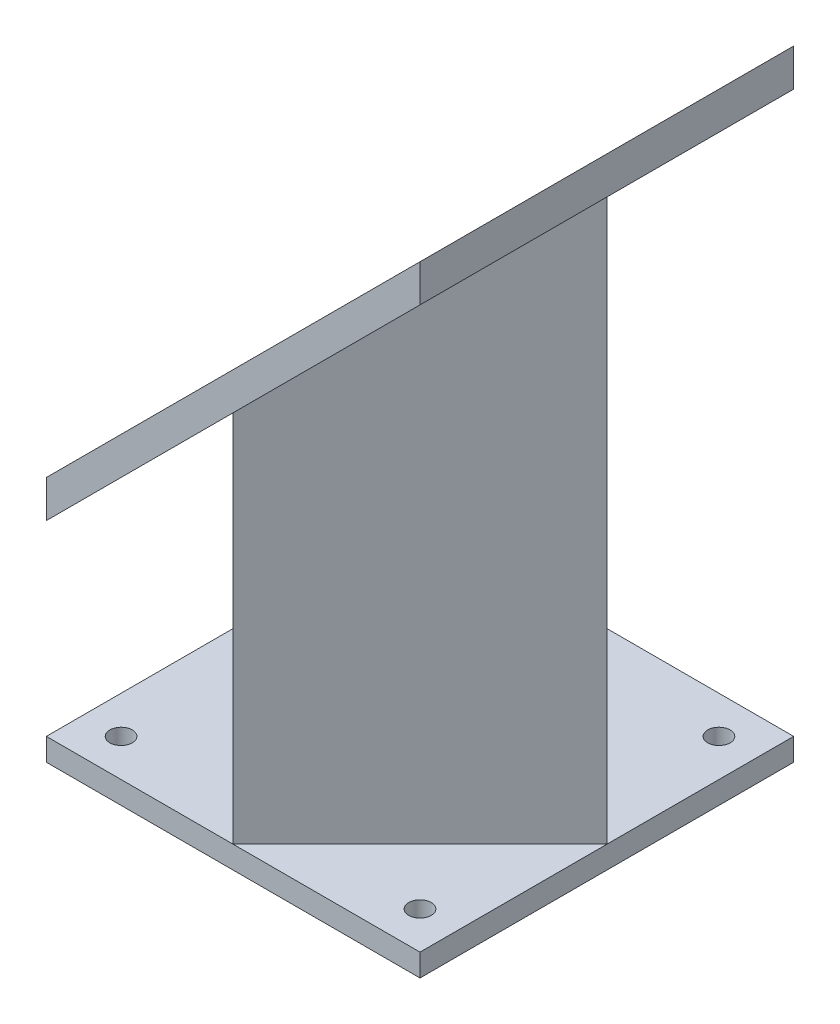
SolidWorks part; units mm, degrees
ref_plane "Front Plane" through (0, 0, 0) normal (0, 0, 1) x (1, 0, 0)
ref_plane "Top Plane" through (0, 0, 0) normal (0, 1, 0) x (1, 0, 0)
ref_plane "Right Plane" through (0, 0, 0) normal (1, 0, 0) x (0, 0, -1)
sketch "Sketch1" plane through (0, 0, 0) normal (0, 1, 0) x (1, 0, 0)
  line L1 (-25, -25) -> (25, -25)
  line L2 (-25, -25) -> (-25, 25)
  line L3 (-25, 25) -> (25, 25)
  line L4 (25, -25) -> (25, 25)
  line L5 (-25, -25) -> (25, 25) construction
  line L6 (-25, 25) -> (25, -25) construction
  circle A0 centre (-20, -20) radius 1.5
  circle A1 centre (-20, 20) radius 1.5
  circle A2 centre (20, 20) radius 1.5
  circle A3 centre (20, -20) radius 1.5
  point P0 (0, 0)
  point P17 (0, 0)
  dimension "D3" = 3
  dimension "D4" = 40
  dimension "D1" = 50
  dimension "D2" = 4
extrude "Boss-Extrude1" add sketch "Sketch1" along normal blind 3
sketch "Sketch2" plane through (0, 3, 0) normal (0, 1, 0) x (1, 0, 0)
  line L0 (25, 25) -> (-25, 25) construction
  line L1 (0, 25) -> (-25, 0)
  line L2 (-25, 0) -> (0, -25)
  line L3 (0, -25) -> (25, 0)
  line L4 (25, 0) -> (0, 25)
  line L6 (0, 17.9289) -> (-17.9289, 0)
  line L7 (-17.9289, 0) -> (0, -17.9289)
  line L8 (0, -17.9289) -> (17.9289, 0)
  line L9 (17.9289, 0) -> (0, 17.9289)
  circle A0 centre (0, 0) radius 17.6777 construction
  circle A1 centre (0, 0) radius 12.6777 construction
  dimension "D1" = 5
extrude "Boss-Extrude2" add sketch "Sketch2" along normal blind 75
sketch "Sketch3" plane through (0, 0, 25) normal (0, 0, 1) x (1, 0, 0)
  line L0 (25, 78) -> (-25, 78)
  line L1 (-25, 78) -> (-25, 28)
  line L2 (-25, 78) -> (-25, 3) construction
  line L3 (-25, 28) -> (25, 78)
  dimension "D1" = 45
extrude "Cut-Extrude1" cut sketch "Sketch3" against normal through all
sketch "Sketch4" plane through (-26.5, 26.5, 0) normal (-0.7071, 0.7071, 0) x (0, 0, 1)
  line L0 (0, 2.1213) -> (0, 72.832) construction
  line L1 (-25, 37.4767) -> (25, 37.4767) construction
  line L2 (-17.9289, 37.4767) -> (0, 62.832) construction
  line L3 (-25, 2.1213) -> (25, 2.1213)
  line L4 (-25, 2.1213) -> (-25, 72.832)
  line L5 (-25, 72.832) -> (25, 72.832)
  line L6 (25, 2.1213) -> (25, 72.832)
  line L7 (-25, 2.1213) -> (25, 72.832) construction
  line L8 (-25, 72.832) -> (25, 2.1213) construction
  line L9 (0, 12.1213) -> (-17.9289, 37.4767) construction
  line L10 (17.9289, 37.4767) -> (0, 12.1213) construction
  line L11 (0, 62.832) -> (17.9289, 37.4767) construction
  line L12 (-17.9289, 37.4767) -> (0, 62.832)
  line L13 (0, 12.1213) -> (-17.9289, 37.4767)
  line L14 (17.9289, 37.4767) -> (0, 12.1213)
  line L15 (0, 62.832) -> (17.9289, 37.4767)
  point P8 (0, 37.4767)
extrude "Boss-Extrude3" add sketch "Sketch4" along direction (0, 1, 0) on the side of the normal blind 5
